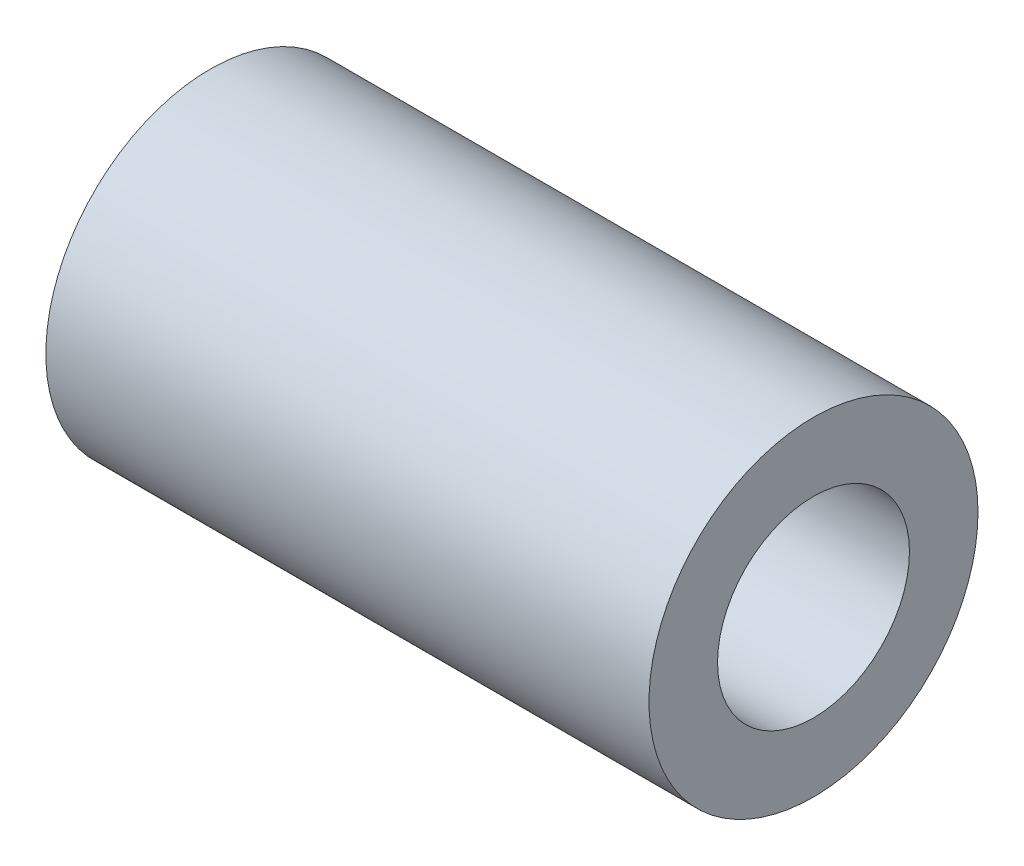
SolidWorks part; units mm, degrees
material "ABS"
ref_plane "Alzado" through (0, 0, 0) normal (0, 0, 1) x (1, 0, 0)
ref_plane "Planta" through (0, 0, 0) normal (0, 1, 0) x (1, 0, 0)
ref_plane "Vista lateral" through (0, 0, 0) normal (1, 0, 0) x (0, 0, -1)
sketch "Croquis1" plane through (0, 0, 0) normal (1, 0, 0) x (0, 0, -1)
  circle A0 centre (0, 0) radius 3
  circle A1 centre (0, 0) radius 1.75
  dimension "D1" = 3.5
  dimension "D2" = 6
extrude "Saliente-Extruir1" add sketch "Croquis1" along normal mid plane 11
